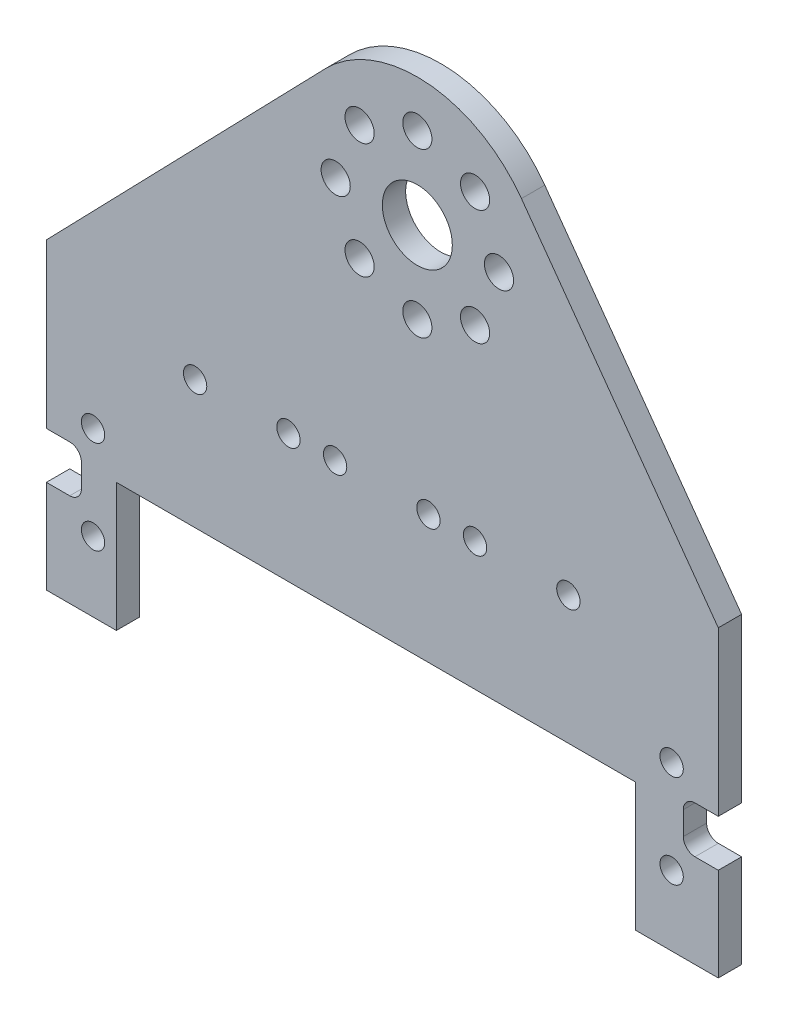
SolidWorks part; units mm, degrees
material "自訂玻璃纖維"
ref_plane "前基準面" through (0, 0, 0) normal (0, 0, 1) x (1, 0, 0)
ref_plane "上基準面" through (0, 0, 0) normal (0, 1, 0) x (1, 0, 0)
ref_plane "右基準面" through (0, 0, 0) normal (1, 0, 0) x (0, 0, -1)
sketch "草圖1" plane through (0, 0, 0) normal (0, 0, 1) x (1, 0, 0)
  line L0 (25.8, -18) -> (25.8, -17)
  line L1 (-31.8, -17) -> (-7.8981, 7.6564)
  line L2 (25.8, -17) -> (8.9259, 6.4287)
  line L4 (-31.8, -18) -> (-31.8, -31)
  line L5 (-25.8, -32) -> (18.7, -32)
  line L6 (18.7, -32) -> (18.7, -43)
  line L9 (-25.8, -32) -> (-25.8, -43)
  line L10 (25.8, -18) -> (25.8, -31)
  line L13 (-31.8, -36) -> (-31.8, -42)
  line L14 (-30.8, -43) -> (-26.8, -43)
  line L15 (18.7, -43) -> (19.7, -43)
  line L16 (20.7, -43) -> (24.8, -43)
  line L17 (25.8, -42) -> (25.8, -36)
  line L18 (-31.8, -17) -> (-31.8, -18)
  line L20 (19.7, -43) -> (20.7, -43)
  line L21 (25.8, -42) -> (25.8, -43)
  line L22 (25.8, -43) -> (24.8, -43)
  line L26 (-25.8, -43) -> (-26.8, -43)
  line L27 (-28.8, -32) -> (-28.8, -34)
  line L28 (-30.8, -43) -> (-31.8, -43)
  line L29 (-31.8, -43) -> (-31.8, -42)
  line L30 (-31.8, -31) -> (-29.8, -31)
  line L31 (22.8, -32) -> (22.8, -34)
  line L32 (-31.8, -35) -> (-29.8, -35)
  line L33 (-31.8, -35) -> (-31.8, -36)
  line L34 (25.8, -31) -> (23.8, -31)
  line L36 (25.8, -35) -> (23.8, -35)
  line L37 (25.8, -35) -> (25.8, -36)
  circle A0 centre (0, 0) radius 3
  circle A1 centre (0, 7) radius 1.25
  circle A2 centre (4.9497, 4.9497) radius 1.25
  circle A3 centre (7, 0) radius 1.25
  circle A4 centre (4.9497, -4.9497) radius 1.25
  circle A5 centre (0, -7) radius 1.25
  circle A6 centre (-4.9497, -4.9497) radius 1.25
  circle A7 centre (-7, 0) radius 1.25
  circle A8 centre (-4.9497, 4.9497) radius 1.25
  arc A9 (8.9259, 6.4287) -> (-7.8981, 7.6564) centre (0, 0) ccw
  circle A10 centre (-27.8, -29) radius 1
  circle A11 centre (-27.8, -37) radius 1
  circle A12 centre (21.8, -37) radius 1
  circle A13 centre (21.8, -29) radius 1
  arc A14 (-29.8, -31) -> (-28.8, -32) centre (-29.8, -32) cw
  arc A15 (-28.8, -34) -> (-29.8, -35) centre (-29.8, -34) cw
  arc A16 (23.8, -31) -> (22.8, -32) centre (23.8, -32) ccw
  arc A17 (22.8, -34) -> (23.8, -35) centre (23.8, -34) ccw
  circle A18 centre (-19.05, -21) radius 1
  circle A19 centre (-11.05, -21) radius 1
  circle A20 centre (4.95, -21) radius 1
  circle A21 centre (12.95, -21) radius 1
  circle A24 centre (-7.05, -21) radius 1
  circle A25 centre (0.95, -21) radius 1
  point P6 (25.8, -17)
  point P21 (0, 0)
  point P46 (25.8, -37)
  point P49 (25.8, -17)
  point P52 (-31.8, -17)
  point P55 (-31.8, -37)
  point P58 (-25.8, -37)
  point P77 (-31.8, -43)
  dimension "D1" = 6
  dimension "D2" = 2.5
  dimension "D3" = 7
  dimension "D5" = 22
  dimension "D6" = 2
  dimension "D13" = 8
  dimension "D14" = 2
  dimension "D15" = 4
  dimension "D16" = 7
  dimension "D17" = 8
  dimension "D19" = 2
  dimension "D20" = 8
  dimension "D21" = 8
  dimension "D22" = 2
  dimension "D23" = 2
  dimension "D24" = 2
  dimension "D25" = 4
  dimension "D26" = 4
  dimension "D11" = 6
  dimension "D27" = 24.75
  dimension "D28" = 4
  dimension "D29" = 6
  dimension "D32" = 2
  dimension "D33" = 4
  dimension "D34" = 4
  dimension "D35" = 0
  dimension "D36" = 0
  dimension "D7" = 57.6
  dimension "D8" = 25.8
  dimension "D9" = 20
  dimension "D10" = 6
  dimension "D12" = 4
  dimension "D18" = 18
  dimension "D30" = 2
  dimension "D31" = 8
  dimension "D4" = 8
extrude "填料-伸長1" add sketch "草圖1" along normal blind 2
